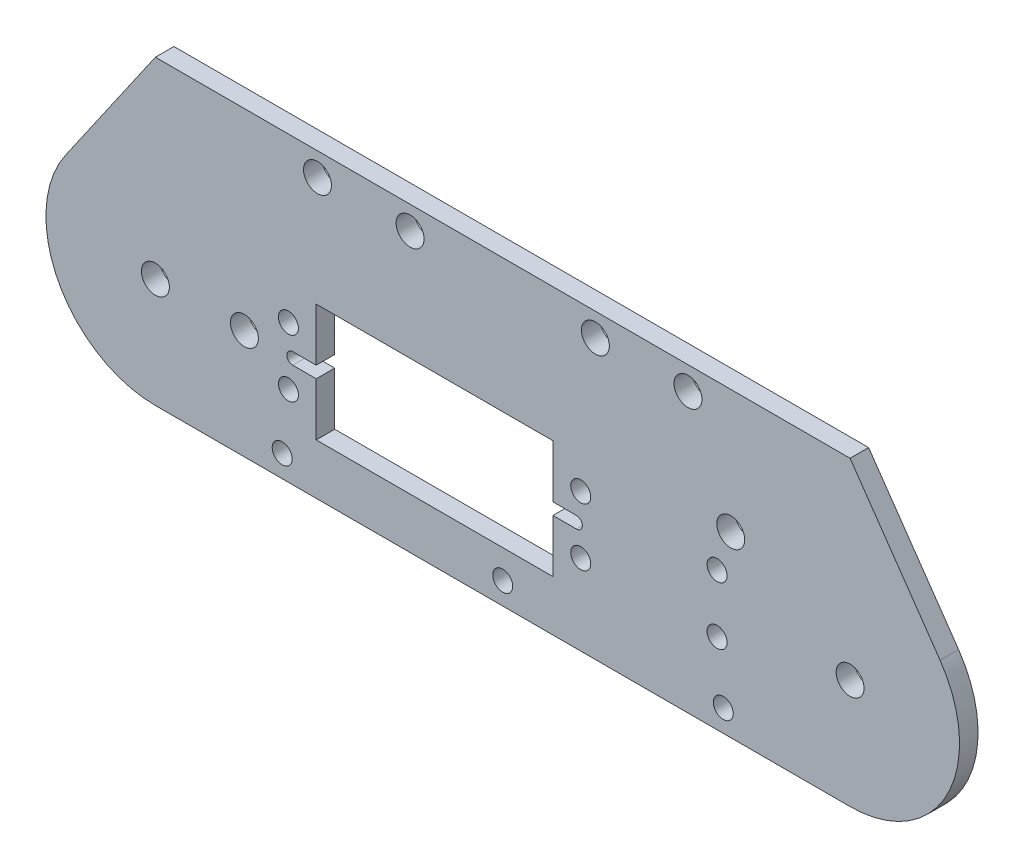
SolidWorks part; units mm, degrees
ref_plane "Front Plane" through (0, 0, 0) normal (0, 0, 1) x (1, 0, 0)
ref_plane "Top Plane" through (0, 0, 0) normal (0, 1, 0) x (1, 0, 0)
ref_plane "Right Plane" through (0, 0, 0) normal (1, 0, 0) x (0, 0, -1)
sketch "Sketch1" plane through (0, 0, 0) normal (0, 0, 1) x (1, 0, 0)
  line L8 (0, 18.9078) -> (120.015, 18.9078) construction
  line L18 (120.015, 52.1157) -> (0, 52.1157)
  line L37 (0, 0) -> (120.015, 0)
  line L54 (120.015, 52.1157) -> (135.5587, 29.6734)
  line L55 (60.0075, 52.1157) -> (60.0075, 18.9078) construction
  line L56 (0, 52.1157) -> (-15.5437, 29.6734)
  circle A21 centre (120.015, 18.9078) radius 2.413
  circle A22 centre (0, 18.9078) radius 2.413
  circle A24 centre (15.3729, 18.9078) radius 2.413
  arc A25 (135.5587, 29.6734) -> (120.015, 0) centre (120.015, 18.9078) cw
  arc A26 (0, 0) -> (-15.5437, 29.6734) centre (0, 18.9078) cw
  dimension "D5" = 18.9078
  dimension "D3" = 52.1157
  dimension "D2" = 4.826
  dimension "D1" = 120.015
  dimension "D4" = 15.3729
  dimension "D7" = 120.015
extrude "Boss-Extrude1" add sketch "Sketch1" along normal blind 3.2004
sketch "Sketch2" plane through (0, 0, 0) normal (0, 0, -1) x (-1, 0, 0)
  line L1 (-60.0075, 52.1157) -> (-60.0075, 48.1152) construction
  line L28 (-92.0115, 48.1152) -> (-76.0095, 48.1152) construction
  line L29 (-76.0095, 48.1152) -> (-44.0055, 48.1152) construction
  line L30 (-44.0055, 48.1152) -> (-28.0035, 48.1152) construction
  line L32 (-120.015, 52.1157) -> (0, 52.1157) construction
  circle A0 centre (-92.0115, 48.1152) radius 2.413
  circle A1 centre (-76.0095, 48.1152) radius 2.413
  circle A2 centre (-44.0055, 48.1152) radius 2.413
  circle A3 centre (-28.0035, 48.1152) radius 2.413
  point P11 (-36.0045, 48.1152)
  point P16 (-84.0105, 48.1152)
  dimension "D3" = 4.826
  dimension "D1" = 4.0005
  dimension "D2" = 16.002
  dimension "D4" = 48.006
extrude "Cut-Extrude1" cut sketch "Sketch2" against normal blind 3.2004
sketch "Sketch5" plane through (0, 0, 0) normal (0, 0, -1) x (-1, 0, 0)
  line L0 (0, 18.9078) -> (-120.015, 18.9078) construction
  line L6 (-68.6783, 29.0678) -> (-68.6783, 8.7478)
  line L7 (-27.7843, 29.0678) -> (-27.7843, 8.7478)
  line L12 (-48.2313, 29.0678) -> (-48.2313, 8.7478) construction
  line L13 (-73.4813, 13.9078) -> (-73.4813, 23.9078) construction
  line L14 (-22.9813, 13.9078) -> (-22.9813, 23.9078) construction
  line L15 (-73.4813, 18.9078) -> (-22.9813, 18.9078) construction
  line L21 (-68.6783, 8.7478) -> (-27.7843, 8.7478)
  line L25 (-68.6783, 29.0678) -> (-27.7843, 29.0678)
  circle A0 centre (-73.4813, 23.9078) radius 1.7272
  circle A1 centre (-22.9813, 13.9078) radius 1.7272
  circle A2 centre (-22.9813, 23.9078) radius 1.7272
  circle A3 centre (-73.4813, 13.9078) radius 1.7272
  circle A4 centre (0, 18.9078) radius 2.413 construction
  point P9 (-48.2313, 18.9078)
  dimension "D2" = 3.4544
  dimension "D3" = 40.894
  dimension "D1" = 50.5
  dimension "D4" = 20.32
  dimension "D5" = 48.2313
  dimension "D7" = 10
extrude "Cut-Extrude3" cut sketch "Sketch5" against normal through all
sketch "Sketch6" plane through (0, 0, 3.2004) normal (0, 0, 1) x (1, 0, 0)
  line L0 (97.0337, 18.9078) -> (73.4813, 18.9078) construction
  line L2 (73.4813, 13.9078) -> (73.4813, 23.9078) construction
  line L3 (73.4813, 18.9078) -> (22.9813, 18.9078) construction
  line L4 (23.7203, 19.9238) -> (27.7843, 19.9238)
  line L5 (23.7203, 19.9238) -> (23.7203, 17.8918) construction
  line L6 (97.0337, 23.9078) -> (97.0337, 13.9078) construction
  line L7 (23.7203, 17.8918) -> (27.7843, 17.8918)
  line L8 (27.7843, 19.9238) -> (27.7843, 17.8918)
  line L9 (68.6783, 19.9238) -> (72.7423, 19.9238)
  line L10 (68.6783, 19.9238) -> (68.6783, 17.8918)
  line L11 (68.6783, 17.8918) -> (72.7423, 17.8918)
  line L12 (72.7423, 19.9238) -> (72.7423, 17.8918) construction
  line L13 (27.7843, 8.7478) -> (27.7843, 29.0678) construction
  line L14 (68.6783, 29.0678) -> (68.6783, 8.7478) construction
  circle A3 centre (97.0337, 23.9078) radius 1.7272
  circle A4 centre (97.0337, 13.9078) radius 1.7272
  arc A6 (72.7423, 19.9238) -> (72.7423, 17.8918) centre (72.7423, 18.9078) cw
  arc A7 (23.7203, 19.9238) -> (23.7203, 17.8918) centre (23.7203, 18.9078) ccw
  point P22 (27.7843, 18.9078)
  point P23 (68.6783, 18.9078)
  dimension "D1" = 3.4544
  dimension "D2" = 23.5524
  dimension "D4" = 4.064
  dimension "D5" = 2.032
extrude "Cut-Extrude4" cut sketch "Sketch6" against normal up to surface (3.2004 mm away) up to face at (71.7541, 23.9078, 0)
sketch "Sketch7" plane through (0, 0, 0) normal (0, 0, -1) x (-1, 0, 0)
  line L0 (-99.4008, 30.8094) -> (-120.015, 18.9078) construction
  line L1 (0, 0) -> (-120.015, 0) construction
  circle A0 centre (-99.4008, 30.8094) radius 2.413
  circle A1 centre (-120.015, 18.9078) radius 2.413 construction
  dimension "D3" = 4.826
  dimension "D1" = 30
  dimension "D2" = 23.8032
extrude "Cut-Extrude5" cut sketch "Sketch7" against normal up to surface (3.2004 mm away) up to face at (98.7609, 13.9078, 3.2004)
sketch "Sketch8" plane through (0, 0, 3.2004) normal (0, 0, 1) x (1, 0, 0)
  line L0 (21.9075, 3.81) -> (98.1075, 3.81) construction
  line L1 (60.0075, 7.62) -> (60.0075, 0) construction
  line L2 (0, 0) -> (120.015, 0) construction
  circle A0 centre (21.9075, 3.81) radius 1.7272
  circle A1 centre (60.0075, 3.81) radius 1.7272
  circle A2 centre (98.1075, 3.81) radius 1.7272
  point P6 (60.0075, 3.81)
  dimension "D3" = 3.4544
  dimension "D1" = 76.2
  dimension "D2" = 7.62
extrude "Cut-Extrude6" cut sketch "Sketch8" against normal up to surface (3.2004 mm away) up to face at (96.9878, 30.8094, 0)
